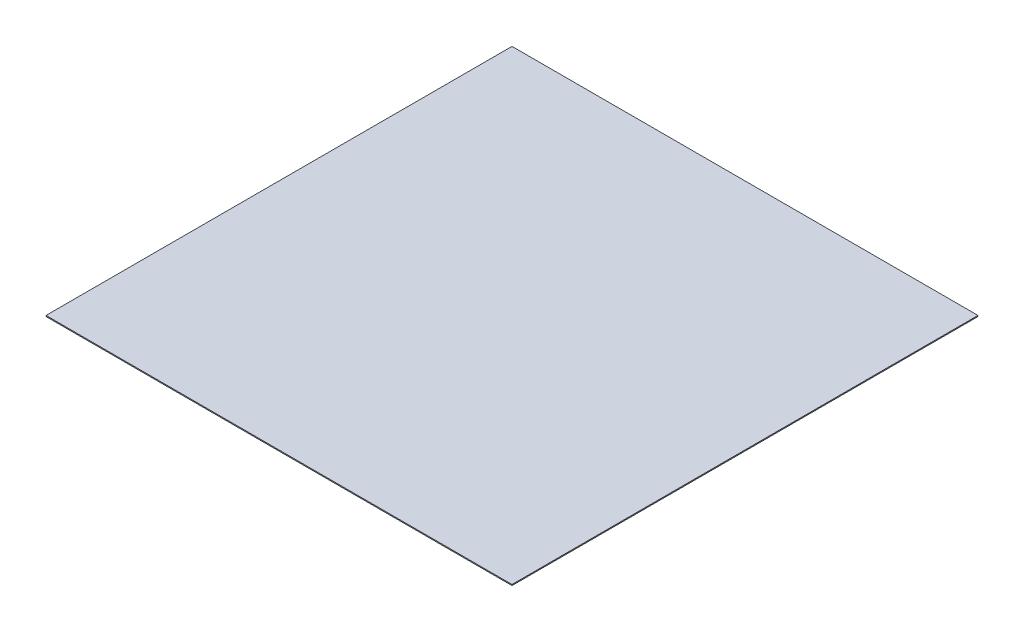
SolidWorks part; units mm, degrees
material "Kapton HN"
ref_plane "Front Plane" through (0, 0, 0) normal (0, 0, 1) x (1, 0, 0)
ref_plane "Top Plane" through (0, 0, 0) normal (0, 1, 0) x (1, 0, 0)
ref_plane "Right Plane" through (0, 0, 0) normal (1, 0, 0) x (0, 0, -1)
sketch "Sketch1" plane through (0, 0, 0) normal (0, 1, 0) x (1, 0, 0)
  line L1 (-69.85, -69.85) -> (69.85, -69.85)
  line L2 (-69.85, -69.85) -> (-69.85, 69.85)
  line L3 (-69.85, 69.85) -> (69.85, 69.85)
  line L4 (69.85, -69.85) -> (69.85, 69.85)
  line L5 (-69.85, -69.85) -> (69.85, 69.85) construction
  line L6 (-69.85, 69.85) -> (69.85, -69.85) construction
  point P0 (0, 0)
  dimension "D1" = 139.7
extrude "Boss-Extrude1" add sketch "Sketch1" along normal mid plane 0.3
